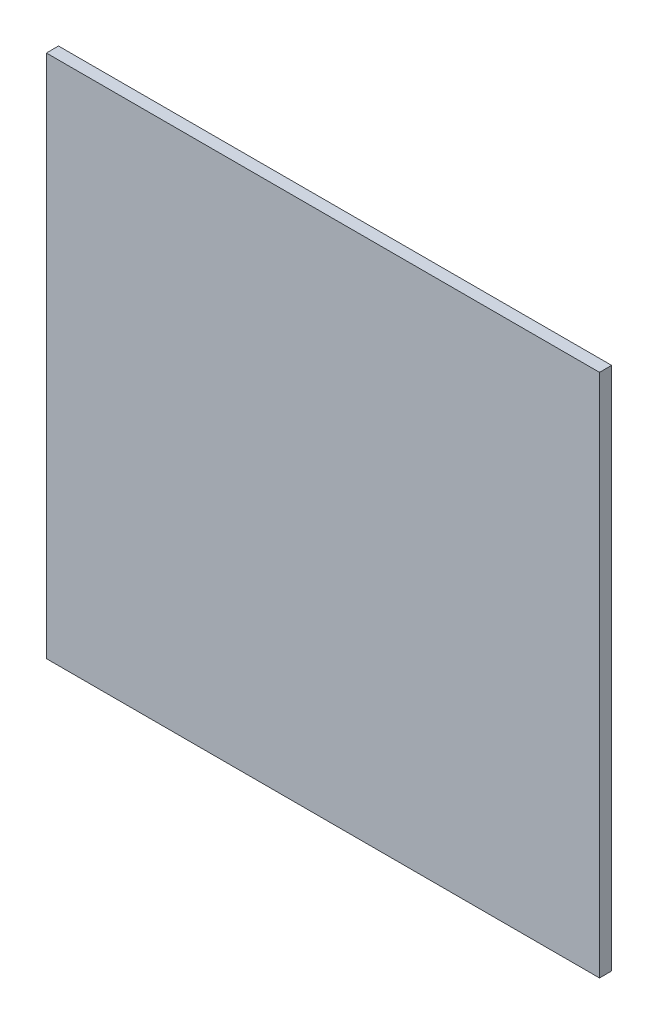
SolidWorks part; units mm, degrees
ref_plane "Front Plane" through (0, 0, 0) normal (0, 0, 1) x (1, 0, 0)
ref_plane "Top Plane" through (0, 0, 0) normal (0, 1, 0) x (1, 0, 0)
ref_plane "Right Plane" through (0, 0, 0) normal (1, 0, 0) x (0, 0, -1)
sketch "Sketch1" plane through (0, 0, 0) normal (0, 0, 1) x (1, 0, 0)
  line L1 (-145, 137.5) -> (145, 137.5)
  line L2 (-145, 137.5) -> (-145, -137.5)
  line L3 (-145, -137.5) -> (145, -137.5)
  line L4 (145, 137.5) -> (145, -137.5)
  line L5 (-145, 137.5) -> (145, -137.5) construction
  line L6 (-145, -137.5) -> (145, 137.5) construction
  point P0 (0, 0)
  dimension "D1" = 290
  dimension "D2" = 275
extrude "Boss-Extrude1" add sketch "Sketch1" along normal blind 6.35
